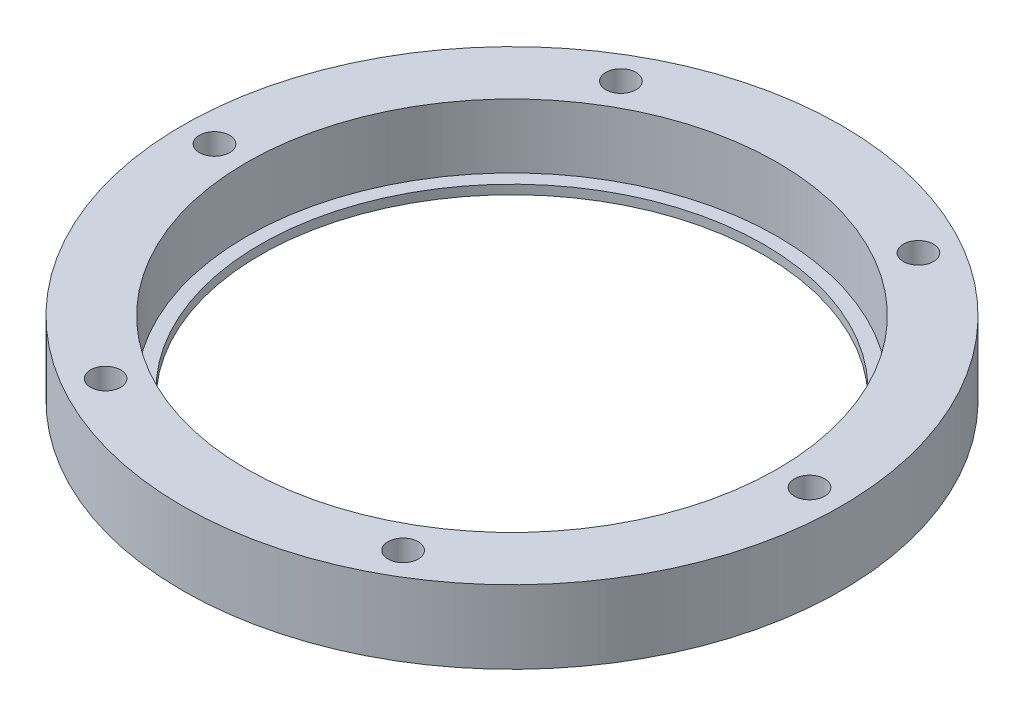
SolidWorks part; units mm, degrees
material "6061 合金"
ref_plane "前视基准面" through (0, 0, 0) normal (0, 0, 1) x (1, 0, 0)
ref_plane "上视基准面" through (0, 0, 0) normal (0, 1, 0) x (1, 0, 0)
ref_plane "右视基准面" through (0, 0, 0) normal (1, 0, 0) x (0, 0, -1)
sketch "草图2" plane through (0, 0, 0) normal (0, 1, 0) x (1, 0, 0)
  circle A0 centre (0, 0) radius 36
  circle A1 centre (0, 0) radius 29
  dimension "D1" = 7
  dimension "D2" = 58
extrude "凸台-拉伸1" add sketch "草图2" along normal blind 7
sketch "草图3" plane through (0, 0, 0) normal (0, -1, 0) x (1, 0, 0)
  circle A0 centre (0, 0) radius 27.5
  circle A1 centre (0, 0) radius 36
  circle A2 centre (0, 0) radius 36
  circle A3 centre (0, 0) radius 29 construction
  dimension "D2" = 1.5
  dimension "D1" = 0
extrude "凸台-拉伸2" add sketch "草图3" along normal blind 1
hole_wizard "M4 螺纹孔1" positions "草图4" profile "草图5" tap size "M4" standard "GB" end condition through all
sketch "草图4" plane through (0, 7, 0) normal (0, 1, 0) x (1, 0, 0)
  circle A0 centre (0, 0) radius 32.5 construction
  circle A1 centre (0, 0) radius 36 construction
  point P0 (-16.25, 28.1458)
  point P26 (16.25, 28.1458)
  point P27 (32.5, 0)
  point P28 (16.25, -28.1458)
  point P29 (-16.25, -28.1458)
  point P30 (-32.5, 0)
  dimension "D1" = 3.5
  dimension "D2" = 6
sketch "草图5" plane through (-16.25, 7, -28.1458) normal (1, 0, 0) x (0, 0, 1)
  line L0 (0, 0) -> (0, 8)
  line L1 (0, 8) -> (1.65, 8)
  line L2 (1.65, 8) -> (1.65, 0)
  line L5 (1.65, 0) -> (0, 0)
  line L11 (0, -6.35) -> (0, 107.95) construction
  dimension "通孔螺纹孔钻头直径" = 3.3
  dimension "通孔螺纹孔钻头深度" = 8
cosmetic thread "孔螺蚊线1" parameters "D1"=12, "D2"=4.3
cosmetic thread "孔螺蚊线2" parameters "D1"=12, "D2"=4.3
cosmetic thread "孔螺蚊线3" parameters "D1"=12, "D2"=4.3
cosmetic thread "孔螺蚊线4" parameters "D1"=12, "D2"=4.3
cosmetic thread "孔螺蚊线5" parameters "D1"=12, "D2"=4.3
cosmetic thread "孔螺蚊线6" parameters "D1"=12, "D2"=4.3
